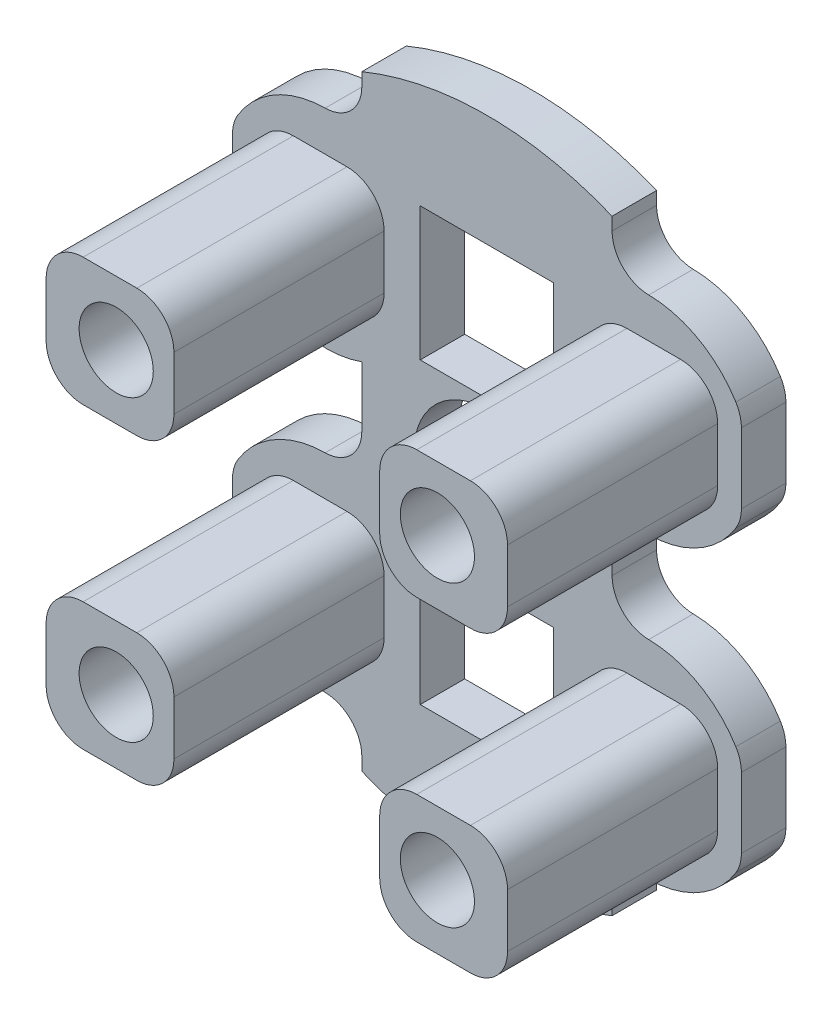
SolidWorks part; units mm, degrees
ref_plane "Front Plane" through (0, 0, 0) normal (0, 0, 1) x (1, 0, 0)
ref_plane "Top Plane" through (0, 0, 0) normal (0, 1, 0) x (1, 0, 0)
ref_plane "Right Plane" through (0, 0, 0) normal (1, 0, 0) x (0, 0, -1)
sketch "Sketch2" plane through (0, 0, 0) normal (0, 0, 1) x (1, 0, 0)
  line L0 (-22.8016, -7.5065) -> (-26.9585, -9.9065) construction
  line L1 (-17.9016, -15.9935) -> (-22.8016, -7.5065) construction
  line L2 (-17.9016, -15.9935) -> (-22.0585, -18.3935) construction
  line L3 (-22.0585, -18.3935) -> (-26.9585, -9.9065) construction
  line L4 (-17.9016, 15.9935) -> (-22.0585, 18.3935) construction
  line L5 (-22.8016, 7.5065) -> (-17.9016, 15.9935) construction
  line L6 (-22.8016, 7.5065) -> (-26.9585, 9.9065) construction
  line L7 (-26.9585, 9.9065) -> (-22.0585, 18.3935) construction
  line L8 (-23.5, 4.9) -> (-28.3, 4.9) construction
  line L9 (-23.5, -4.9) -> (-23.5, 4.9) construction
  line L10 (-23.5, -4.9) -> (-28.3, -4.9) construction
  line L11 (-28.3, -4.9) -> (-28.3, 4.9) construction
  line L12 (4.5, 14.5625) -> (-4.5, 14.5625) construction
  line L13 (4.5, 14.5625) -> (4.5, 5.5625) construction
  line L14 (4.5, 5.5625) -> (-4.5, 5.5625) construction
  line L15 (-4.5, 14.5625) -> (-4.5, 5.5625) construction
  line L16 (-6.4367, -21.5597) -> (-6.4367, 21.5597) construction
  line L17 (6.4367, -21.5597) -> (6.4367, 21.5597) construction
  line L18 (23.5, -4.9) -> (23.5, 4.9) construction
  line L19 (23.5, 4.9) -> (28.3, 4.9) construction
  line L20 (28.3, -4.9) -> (28.3, 4.9) construction
  line L21 (23.5, -4.9) -> (28.3, -4.9) construction
  line L22 (17.9016, -15.9935) -> (22.8016, -7.5065) construction
  line L23 (22.8016, -7.5065) -> (26.9585, -9.9065) construction
  line L24 (22.0585, -18.3935) -> (26.9585, -9.9065) construction
  line L25 (17.9016, -15.9935) -> (22.0585, -18.3935) construction
  line L26 (22.8016, 7.5065) -> (17.9016, 15.9935) construction
  line L27 (17.9016, 15.9935) -> (22.0585, 18.3935) construction
  line L28 (26.9585, 9.9065) -> (22.0585, 18.3935) construction
  line L29 (22.8016, 7.5065) -> (26.9585, 9.9065) construction
  line L30 (4.5, -14.5625) -> (4.5, -5.5625) construction
  line L31 (4.5, -14.5625) -> (-4.5, -14.5625) construction
  line L32 (-4.5, -14.5625) -> (-4.5, -5.5625) construction
  line L33 (4.5, -5.5625) -> (-4.5, -5.5625) construction
  circle A0 centre (0, 0) radius 4.9125 construction
  arc A1 (-6.4367, 21.5597) -> (-6.4367, -21.5597) centre (0, 0) ccw construction
  arc A2 (6.4367, -21.5597) -> (6.4367, 21.5597) centre (0, 0) ccw construction
  circle A3 centre (0, 0) radius 29.64 construction
sketch "Sketch3" plane through (0, 0, 0) normal (0, 0, 1) x (1, 0, 0)
  line L1 (6.157, -22.5) -> (-6.157, -22.5)
  line L2 (6.157, -22.5) -> (6.157, 22.5)
  line L3 (6.157, 22.5) -> (-6.157, 22.5)
  line L4 (-6.157, -22.5) -> (-6.157, 22.5)
  line L5 (6.157, -22.5) -> (-6.157, 22.5) construction
  line L6 (6.157, 22.5) -> (-6.157, -22.5) construction
  line L7 (4.5, 14.5625) -> (-4.5, 14.5625)
  line L8 (4.5, 14.5625) -> (4.5, 5.5625)
  line L9 (4.5, 5.5625) -> (-4.5, 5.5625)
  line L10 (-4.5, 14.5625) -> (-4.5, 5.5625)
  line L11 (4.5, -5.5625) -> (-4.5, -5.5625)
  line L12 (4.5, -5.5625) -> (4.5, -14.5625)
  line L13 (4.5, -14.5625) -> (-4.5, -14.5625)
  line L14 (-4.5, -5.5625) -> (-4.5, -14.5625)
  line L15 (-17.157, -22.5423) -> (17.157, -22.5423)
  line L16 (-17.157, -22.5423) -> (-17.157, 22.5423)
  line L17 (-17.157, 22.5423) -> (17.157, 22.5423)
  line L18 (17.157, -22.5423) -> (17.157, 22.5423)
  line L19 (-17.157, -22.5423) -> (17.157, 22.5423) construction
  line L20 (-17.157, 22.5423) -> (17.157, -22.5423) construction
  circle A0 centre (0, 0) radius 22.1
  circle A1 centre (0, 0) radius 4.9125
  dimension "D1" = 11
  dimension "D2" = 44.2
extrude "Boss-Extrude1" add sketch "Sketch3" against normal blind 3 contours L4 A0 L16 | L2 A0 L4 A1 L14 L11 L12 L13 L10 L7 L8 L9 | L18 A0 L2
sketch "Sketch4" plane through (0, 0, 0) normal (0, 0, 1) x (1, 0, 0)
  line L0 (4.5, 14.5625) -> (4.5, 5.5625) construction
  line L1 (15.5553, 14.3718) -> (6.9367, 14.3718)
  line L2 (15.5553, 14.3718) -> (15.5553, 5.7532)
  line L3 (15.5553, 5.7532) -> (6.9367, 5.7532)
  line L4 (6.9367, 14.3718) -> (6.9367, 5.7532)
  line L5 (15.5553, 14.3718) -> (6.9367, 5.7532) construction
  line L6 (15.5553, 5.7532) -> (6.9367, 14.3718) construction
  line L8 (6.9367, 10.0625) -> (6.4367, 10.0625)
  line L10 (6.4367, -21.5597) -> (6.4367, 21.5597) construction
  point P0 (11.246, 10.0625)
  point P7 (4.5, 10.0625)
  line M4 (17.157, -13.9301) -> (17.157, 13.9301)
  arc M5 (17.157, 13.9301) -> (-17.157, 13.9301) centre (0, 0) ccw
  dimension "D1" = 0.5
extrude "Boss-Extrude2" add sketch "Sketch4" along normal blind 14.17 contours L1 L4 L3 M4 M5
sketch "Sketch5" plane through (0, 0, -3) normal (0, 0, -1) x (-1, 0, 0)
  line L0 (-4.5, 10.0625) -> (-17.157, 10.0625)
  line L2 (-10.8285, 10.0625) -> (-10.8285, 19.2654)
  line L3 (-4.5, 14.5625) -> (-4.5, 5.5625) construction
  line L4 (-17.157, -13.9301) -> (-17.157, 13.9301) construction
  arc A1 (17.157, 13.9301) -> (-17.157, 13.9301) centre (0, 0) ccw construction
  circle A2 centre (-10.8285, 10.0625) radius 6
  circle A3 centre (-10.8285, 10.0625) radius 2.5
  dimension "D1" = 12
extrude "Cut-Extrude1" cut sketch "Sketch5" against normal through all contours L0 A3 L2 | L0 A3 | L2 A3 L0
mirror "Mirror1" about plane through (0, 0, 0) normal (0, 1, 0) of "Cut-Extrude1", "Boss-Extrude2"
mirror "Mirror2" about plane through (0, 0, 0) normal (1, 0, 0) of "Mirror1", "Boss-Extrude2", "Cut-Extrude1"
sketch "Sketch6" plane through (0, 0, -3) normal (0, 0, -1) x (-1, 0, 0)
  line L0 (0, 0) -> (0, 10.0625) construction
  line L1 (0, 0) -> (-8.8696, 0) construction
  line L2 (-8.4367, 20.4263) -> (-8.4367, -20.4263)
  line L3 (8.4367, 20.4263) -> (8.4367, -20.4263)
  line L4 (0, 16.9177) -> (0, 19.2654)
  line L6 (8.4367, 0) -> (6.4367, 0)
  line L7 (-10.8285, 17.0625) -> (10.8285, 17.0625)
  line L8 (10.8285, -17.0625) -> (-10.8285, -17.0625)
  line L10 (6.4367, -21.5597) -> (6.4367, 21.5597) construction
  circle A0 centre (-10.8285, 10.0625) radius 7
  circle A1 centre (-10.8285, 10.0625) radius 2.5 construction
  circle A2 centre (10.8285, 10.0625) radius 7
  circle A3 centre (10.8285, -10.0625) radius 7
  circle A4 centre (-10.8285, -10.0625) radius 7
  circle A5 centre (0, 0) radius 22.1
  arc A6 (-17.157, -13.9301) -> (17.157, -13.9301) centre (0, 0) ccw construction
  arc M6 (-17.157, -13.9301) -> (17.157, -13.9301) centre (0, 0) ccw
  line M7 (17.157, -13.9301) -> (17.157, 13.9301)
  arc M8 (17.157, 13.9301) -> (-17.157, 13.9301) centre (0, 0) ccw
  line M9 (-17.157, 13.9301) -> (-17.157, -13.9301)
  dimension "D1" = 2
extrude "Cut-Extrude2" cut sketch "Sketch6" against normal blind 15 contours A4 L2 A0 M9 | L8 A4 L2 M9 M6 | A3 L8 L3 M6 M7 | A3 A2 L3 M7 | A0 L7 L2 M8 M9 | L7 A2 L3 M7 M8
fillet "Fillet1" radius 2.5 31 edges at (8.4367, 17.0625, -1.5) (17.157, 13.0542, -1.5) (17.157, 7.0708, -1.5) (8.4367, 3.4838, -1.5) (6.9367, 14.3718, 7.085) (6.9367, 5.7532, 7.085) (15.5553, 5.7532, 7.085) (15.5553, 14.3718, 7.085) (-8.4367, 17.0625, -1.5) (-17.157, 7.0708, -1.5) (-17.157, 13.0542, -1.5) (-15.5553, 14.3718, 7.085) (-15.5553, 5.7532, 7.085) (-6.9367, 14.3718, 7.085) (-6.9367, 5.7532, 7.085) (-6.9367, -5.7532, 7.085) (-15.5553, -5.7532, 7.085) (-15.5553, -14.3718, 7.085) (-6.9367, -14.3718, 7.085) (-8.4367, -3.4838, -1.5) (-17.157, -13.0542, -1.5) (-17.157, -7.0708, -1.5) (-8.4367, -17.0625, -1.5) (8.4367, -17.0625, -1.5) (6.9367, -5.7532, 7.085) (6.9367, -14.3718, 7.085) (15.5553, -14.3718, 7.085) (15.5553, -5.7532, 7.085) (17.157, -13.0542, -1.5) (17.157, -7.0708, -1.5) (8.4367, -3.4838, -1.5)
